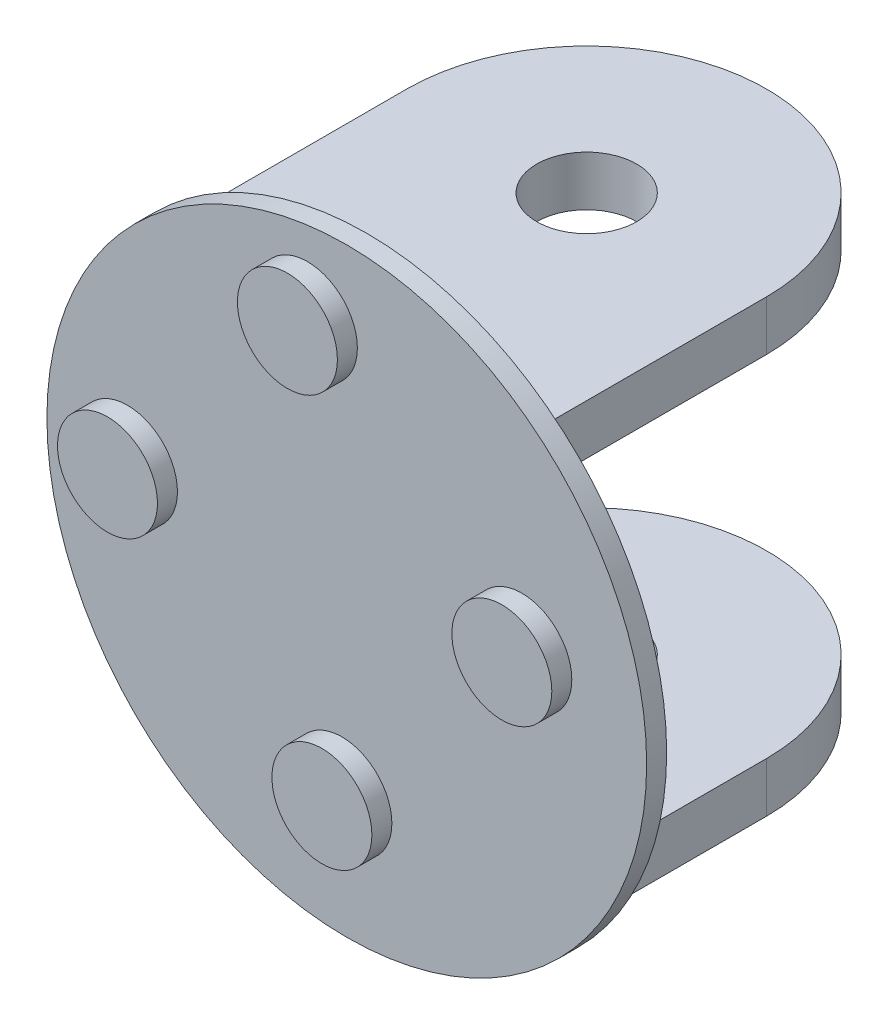
SolidWorks part; units mm, degrees
ref_plane "Ön Düzlem" through (0, 0, 0) normal (0, 0, 1) x (1, 0, 0)
ref_plane "Üst Düzlem" through (0, 0, 0) normal (0, 1, 0) x (1, 0, 0)
ref_plane "Sağ Düzlem" through (0, 0, 0) normal (1, 0, 0) x (0, 0, -1)
sketch "Sketch1" plane through (0, 0, 0) normal (0, 0, 1) x (1, 0, 0)
  circle A0 centre (0, 0) radius 30
  dimension "D1" = 60
extrude "Boss-Extrude1" add sketch "Sketch1" against normal blind 2
sketch "Sketch3" plane through (0, 0, -2) normal (0, 0, -1) x (-1, 0, 0)
  line L0 (-30, 0) -> (30, 0) construction
  line L1 (18, -17.5) -> (-18, -17.5)
  line L2 (18, -17.5) -> (18, -22.5)
  line L3 (18, -22.5) -> (-18, -22.5)
  line L4 (-18, -17.5) -> (-18, -22.5)
  line L5 (18, -17.5) -> (-18, -22.5) construction
  line L6 (18, -22.5) -> (-18, -17.5) construction
  line L7 (0, 30) -> (0, -30) construction
  circle A0 centre (0, 0) radius 30 construction
  point P0 (0, -20)
  point P5 (-30, 0)
  point P6 (30, 0)
  dimension "D1" = 12
  dimension "D2" = 12
  dimension "D3" = 36
  dimension "D4" = 5
  dimension "D5" = 7.5
extrude "Boss-Extrude3" add sketch "Sketch3" along normal blind 22
sketch "Sketch5" plane through (0, -22.5, 0) normal (0, -1, 0) x (1, 0, 0)
  line L0 (18, -24) -> (-18, -24) construction
  line L1 (-18, -24) -> (18, -24)
  arc A0 (-18, -24) -> (18, -24) centre (0, -24) ccw
extrude "Boss-Extrude4" add sketch "Sketch5" against normal up to surface (5 mm away) up to face at (0, -17.5, -13)
sketch "Sketch6" plane through (0, -17.5, 0) normal (0, 1, 0) x (1, 0, 0)
  circle A0 centre (0, 24) radius 5
  dimension "D1" = 10
extrude "Cut-Extrude1" cut sketch "Sketch6" against normal blind 22
mirror "Mirror2" about plane through (0, 0, 0) normal (0, 1, 0) of "Boss-Extrude4", "Cut-Extrude1", "Boss-Extrude3"
sketch "Sketch7" plane through (0, 0, 0) normal (0, 0, 1) x (1, 0, 0)
  line L0 (0, 30) -> (0, -30) construction
  line L1 (-30, 0) -> (30, 0) construction
  circle A0 centre (0, 0) radius 30 construction
  circle A1 centre (-3.94, 21.58) radius 5
  circle A2 centre (-21.94, 0.13) radius 5
  circle A3 centre (-0.49, -17.87) radius 5
  circle A4 centre (17.51, 3.58) radius 5
  point P16 (24.931, 3.3241)
  dimension "D9" = 10
  dimension "D1" = 3.94
  dimension "D2" = 21.58
  dimension "D3" = 0.13
  dimension "D4" = 21.94
  dimension "D5" = 0.49
  dimension "D6" = 17.87
  dimension "D7" = 17.51
  dimension "D8" = 3.58
extrude "Boss-Extrude5" add sketch "Sketch7" along normal blind 2
